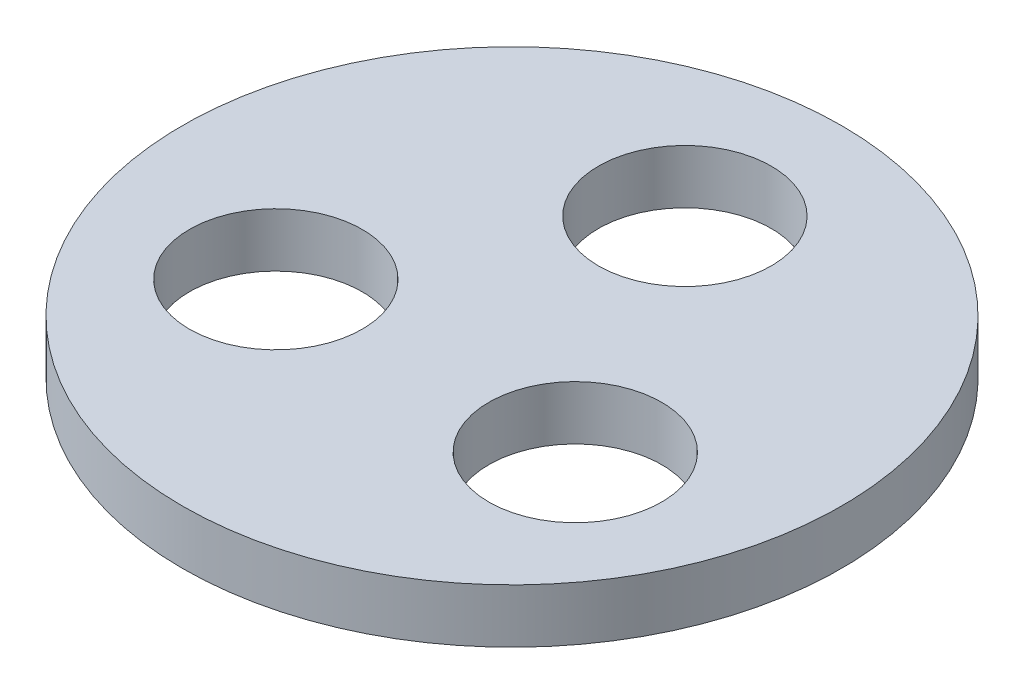
SolidWorks part; units mm, degrees
material "HYPALON"
ref_plane "Front Plane" through (0, 0, 0) normal (0, 0, 1) x (1, 0, 0)
ref_plane "Top Plane" through (0, 0, 0) normal (0, 1, 0) x (1, 0, 0)
ref_plane "Right Plane" through (0, 0, 0) normal (1, 0, 0) x (0, 0, -1)
sketch "Szkic1" plane through (0, 0, 0) normal (0, 1, 0) x (1, 0, 0)
  line L0 (0, 0) -> (0, 32)
  circle A0 centre (0, 0) radius 61
  circle A1 centre (0, 32) radius 16
  circle A2 centre (27.7128, -16) radius 16
  circle A3 centre (-27.7128, -16) radius 16
  point P12 (0, 0)
  dimension "D1" = 122
  dimension "D2" = 32
  dimension "D3" = 32
  dimension "D4" = 3
extrude "Dodanie-wyciągnięcie1" add sketch "Szkic1" along normal blind 10
